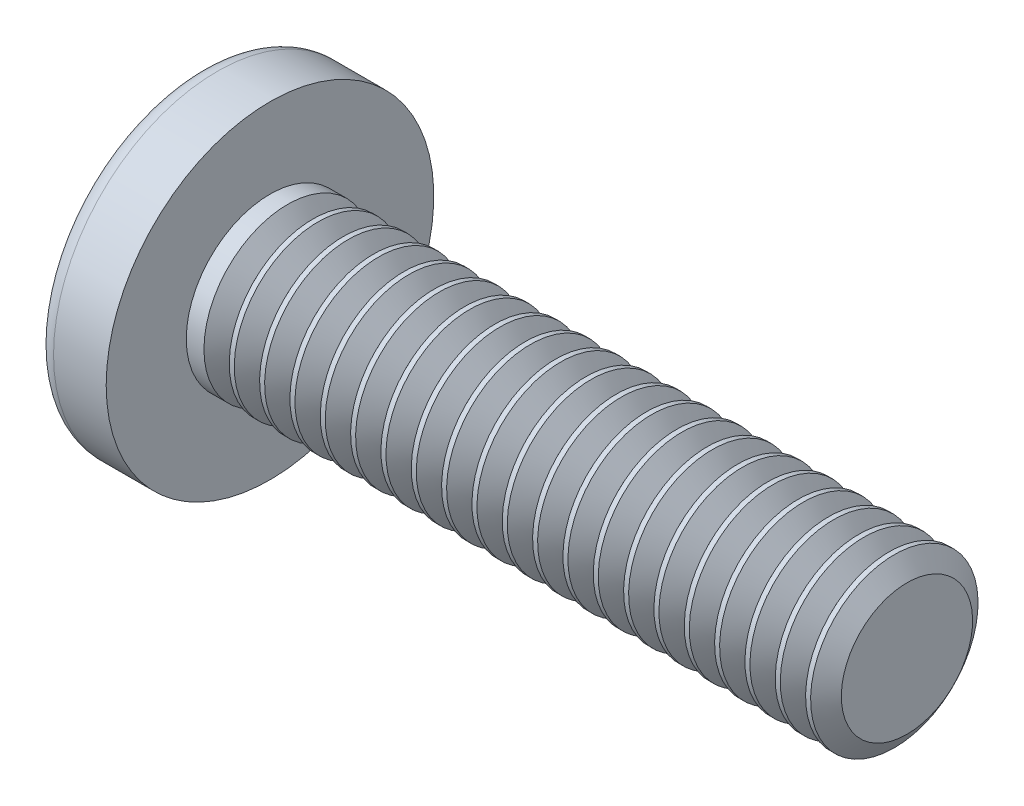
SolidWorks part; units mm, degrees
ref_plane "Plane1" through (0, 0, 0) normal (0, 0, 1) x (1, 0, 0)
ref_plane "Plane2" through (0, 0, 0) normal (0, 1, 0) x (1, 0, 0)
ref_plane "Plane3" through (0, 0, 0) normal (1, 0, 0) x (0, 0, -1)
other "Configuration Table"
sketch "BodySke" plane through (0, 0, 0) normal (0, 0, 1) x (1, 0, 0)
  line L0 (2.4638, 1.7526) -> (2.4638, 3.429)
  line L1 (2.7813, 6.35) -> (2.7813, -3.175) construction
  line L2 (-25.4, 0) -> (127, 0) construction
  line L3 (15.7988, 0) -> (0, 0)
  line L4 (2.4638, 1.7526) -> (15.7988, 1.7526)
  line L5 (15.7988, 1.7526) -> (15.7988, 0)
  line L6 (1.3616, 3.429) -> (2.4638, 3.429)
  line L7 (2.4638, -1.7526) -> (15.7988, -1.7526) construction
  line L8 (3.0988, 6.35) -> (3.0988, -3.175) construction
  arc A0 (1.0521, 3.2702) -> (0, 0) centre (5.6083, 0) ccw
  arc A2 (1.0521, 3.2702) -> (1.3616, 3.429) centre (1.3616, 3.048) cw
  dimension "Head_crown_rad" = 5.6083
  dimension "Head_fillet_rad" = 0.381
  dimension "Diameter" = 3.5052
  dimension "Length" = 13.335
  dimension "Head_ht" = 2.4638
  dimension "Head_dia" = 6.858
  dimension "Advance" = 0.635
  dimension "Thread_nom" = 12.7
revolve "Base-Revolve" add sketch "BodySke" angle 360 about L2
cosmetic thread "ThreadCosmetic" [suppressed] parameters "Thread_length"=12.7, "Thread_minor"=2.7483
sketch "Sketch3" plane through (0, 0, 0) normal (1, 0, 0) x (0, 0, -1)
  line L0 (0.4699, -2.2352) -> (-0.4699, -2.2352)
  line L1 (0.4699, -2.2352) -> (0.4699, 2.2352)
  line L2 (-0.4699, 2.2352) -> (0.4699, 2.2352)
  line L3 (-0.4699, 2.2352) -> (-0.4699, -2.2352)
  dimension "Cross_dia" = 4.4704
  dimension "D1" = 2.2352
  dimension "Cross_width" = 0.9398
  dimension "D2" = 0.4699
ref_plane "Plane4" through (2.4384, 0, 0) normal (1, 0, 0) x (0, 0, -1)
sketch "Sketch4" plane through (2.4384, 0, 0) normal (1, 0, 0) x (0, 0, -1)
  line L0 (0.2349, -0.2349) -> (-0.2349, -0.235)
  line L1 (0.2349, -0.2349) -> (0.2349, 0.2349)
  line L2 (-0.2349, 0.2349) -> (0.2349, 0.2349)
  line L3 (-0.2349, 0.2349) -> (-0.2349, -0.235)
  dimension "D2" = 0.4699
  dimension "D1" = 0.4699
  dimension "D3" = 0.2349
  dimension "D4" = 0.2349
loft "Cut-Loft1" cut profiles "Sketch3", "Sketch4"
pattern_circular "CirPattern1" count 2 every 90 about axis through (0, 0, 0) along (1, 0, 0) of "Cut-Loft1"
sketch "ThdSchSke" plane through (0, 0, 0) normal (0, 0, 1) x (1, 0, 0)
  line L0 (3.0988, -1.3741) -> (2.8338, -1.7526)
  line L1 (3.0988, -1.3741) -> (3.3638, -1.7526)
  line L2 (3.3638, -1.7526) -> (3.3638, -2.1907)
  line L3 (-3.175, 0) -> (5.1513, 0) construction
  line L5 (3.3638, -2.1907) -> (2.8338, -2.1907)
  line L6 (2.8338, -2.1907) -> (2.8338, -1.7526)
  dimension "Diameter" = 3.5052
  dimension "SideAngle" = 55
  dimension "VeeAngle" = 70
  dimension "Thread_minor" = 2.7483
  dimension "Overcut" = 4.3815
  dimension "Start" = 3.0988
revolve "ThreadSchematic" cut sketch "ThdSchSke" angle 360 about L3
pattern_linear "ThdSchPat" count 21 spacing 0.635 along (1, 0, 0) of "ThreadSchematic"
equation "\"D1@Sketch3\" = \"Cross_dia@Sketch3\" / 2"
equation "\"D2@Sketch3\" = \"Cross_width@Sketch3\" / 2"
equation "\"D1@Sketch4\" = \"Cross_width@Sketch3\" *.5"
equation "\"D2@Sketch4\" = \"D1@Sketch4\""
equation "\"D3@Sketch4\" = \"D1@Sketch4\" / 2"
equation "\"D4@Sketch4\" = \"D2@Sketch4\" / 2"
equation "\"Thread_length@ThreadCosmetic\" = ((sgn( (\"Length@BodySke\" - \"Advance@BodySke\" ) - \"Thread_nom@BodySke\" )-1)*( (\"Length@BodySke\" - \"Advance@BodySke\" ) - \"Thread_nom@BodySke\" ))/-2+ \"Thread_nom@BodySke\""
equation "\"Thread_minor@ThdSchSke\" = \"Thread_minor@ThreadCosmetic\""
equation "\"Diameter@ThdSchSke\" = \"Diameter@BodySke\""
equation "\"Overcut@ThdSchSke\" = \"Diameter@BodySke\" * 1.25"
equation "\"Start@ThdSchSke\" = \"Head_ht@BodySke\" + \"Length@BodySke\" - \"Thread_length@ThreadCosmetic\"  '---Non-countersunk---"
equation "\"Num_threads@ThdSchPat\" = int( \"Thread_length@ThreadCosmetic\" / \"Advance@BodySke\" + 0.999 )  + 1"
equation "\"Advance@ThdSchPat\" = \"Thread_length@ThreadCosmetic\" /  (\"Num_threads@ThdSchPat\" - 1) 'relax it"
